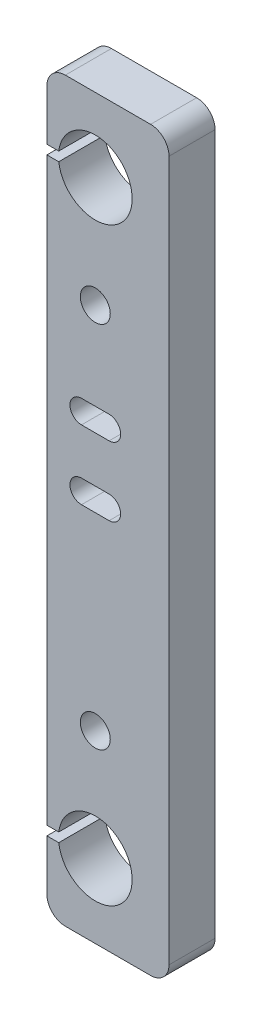
SolidWorks part; units mm, degrees
ref_plane "Front Plane" through (0, 0, 0) normal (0, 0, 1) x (1, 0, 0)
ref_plane "Top Plane" through (0, 0, 0) normal (0, 1, 0) x (1, 0, 0)
ref_plane "Right Plane" through (0, 0, 0) normal (1, 0, 0) x (0, 0, -1)
sketch "Sketch1" plane through (0, 0, 0) normal (0, 0, 1) x (1, 0, 0)
  line L0 (8, 72) -> (8, 8) construction
  line L1 (0, 0) -> (16, 0)
  line L2 (0, 0) -> (0, 80)
  line L3 (0, 80) -> (16, 80)
  line L4 (16, 0) -> (16, 80)
  line L5 (8, 8) -> (8, 0) construction
  line L6 (6.5, 49.25) -> (9.5, 49.25) construction
  line L7 (6.5, 50.5) -> (9.5, 50.5)
  line L8 (6.5, 48) -> (9.5, 48)
  line L9 (6.5, 41.75) -> (9.5, 41.75) construction
  line L10 (6.5, 43) -> (9.5, 43)
  line L11 (6.5, 40.5) -> (9.5, 40.5)
  line L12 (8, 40) -> (16, 40) construction
  circle A0 centre (8, 72) radius 4
  circle A1 centre (8, 8) radius 4
  arc A2 (6.5, 50.5) -> (6.5, 48) centre (6.5, 49.25) ccw
  arc A3 (9.5, 48) -> (9.5, 50.5) centre (9.5, 49.25) ccw
  arc A4 (6.5, 43) -> (6.5, 40.5) centre (6.5, 41.75) ccw
  arc A5 (9.5, 40.5) -> (9.5, 43) centre (9.5, 41.75) ccw
  circle A6 centre (8, 20) radius 1.625
  circle A7 centre (8, 60) radius 1.625
  point P12 (8, 49.25)
  point P17 (8, 41.75)
  dimension "D2" = 8
  dimension "D10" = 3.25
  dimension "D1" = 8
  dimension "D3" = 64
  dimension "D4" = 8
  dimension "D5" = 8
  dimension "D6" = 8
  dimension "D7" = 3
  dimension "D8" = 2.5
  dimension "D9" = 5
  dimension "D11" = 12
  dimension "D12" = 12
extrude "Boss-Extrude1" add sketch "Sketch1" along normal blind 5
sketch "Sketch3" plane through (0, 0, 0) normal (0, 0, -1) x (-1, 0, 0)
  line L0 (-8, 72) -> (0, 72) construction
  line L2 (-8, 72.5) -> (0, 72.5)
  line L3 (-8, 71.5) -> (0, 71.5)
  line L4 (-8, 8) -> (0, 8) construction
  line L5 (-8, 8.5) -> (0, 8.5)
  line L6 (-8, 7.5) -> (0, 7.5)
  line L7 (0, 80) -> (0, 0) construction
  arc A1 (-8, 72.5) -> (-8, 71.5) centre (-8, 72) ccw
  arc A2 (0, 71.5) -> (0, 72.5) centre (0, 72) ccw
  circle A3 centre (-8, 72) radius 4 construction
  arc A4 (-8, 8.5) -> (-8, 7.5) centre (-8, 8) ccw
  arc A5 (0, 7.5) -> (0, 8.5) centre (0, 8) ccw
  point P2 (-4, 8)
  point P4 (-8, 75.8503)
  point P5 (0, 71.9197)
  point P6 (-4, 72)
  point P21 (0, 0)
  point P22 (0, 8.0252)
  dimension "D1" = 1
extrude "Cut-Extrude3" cut sketch "Sketch3" against normal through all
sketch "Sketch4" plane through (0, 0, 0) normal (0, 0, -1) x (-1, 0, 0)
  line L0 (0, 0) -> (-16, 0) construction
  line L1 (0, 80) -> (-2.75, 80)
  line L2 (0, 80) -> (0, 0)
  line L3 (0, 0) -> (-2.75, 0)
  line L4 (-2.75, 80) -> (-2.75, 0)
  circle A0 centre (-8, 60) radius 1.625 construction
  dimension "D1" = 5.25
extrude "Cut-Extrude4" cut sketch "Sketch4" against normal through all
fillet "Fillet1" radius 2 4 edges at (16, 0, 2.5) (16, 80, 2.5) (2.75, 0, 2.5) (2.75, 80, 2.5)
